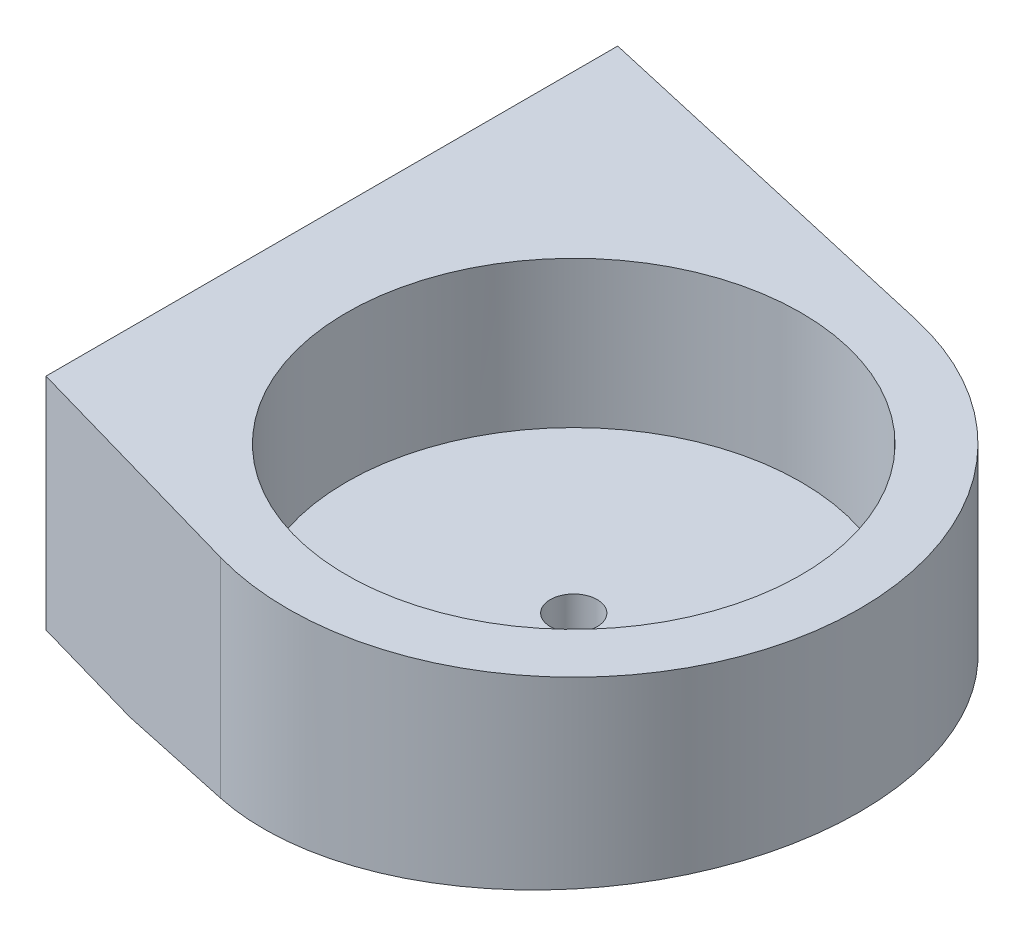
SolidWorks part; units mm, degrees
ref_plane "Front" through (0, 0, 0) normal (0, 0, 1) x (1, 0, 0)
ref_plane "Top" through (0, 0, 0) normal (0, 1, 0) x (1, 0, 0)
ref_plane "Right" through (0, 0, 0) normal (1, 0, 0) x (0, 0, -1)
sketch "Sketch1" plane through (0, 0, 0) normal (0, 1, 0) x (1, 0, 0)
  circle A0 centre (0, 0) radius 15.5
  dimension "D1" = 31
extrude "Boss-Extrude1" add sketch "Sketch1" along normal blind 5
sketch "Sketch2" plane through (0, 0, 0) normal (0, -1, 0) x (1, 0, 0)
  line L0 (-5.3514, 18.7513) -> (-22, 14)
  line L1 (-22, 14) -> (-22, -25)
  line L2 (-22, -25) -> (4.3235, -19.0147)
  circle A3 centre (0, 0) radius 19.5
  arc A4 (4.3235, -19.0147) -> (-5.3514, 18.7513) centre (0, 0) ccw
  point P4 (0, 0)
  point P5 (-25, -28.3121)
  circle M5 centre (0, 0) radius 15.5
  dimension "D4" = 14
  dimension "D2" = 22
  dimension "D3" = 39
  dimension "D1" = 4
extrude "Boss-Extrude2" add sketch "Sketch2" against normal blind 15 contours L2 A4 L0 L1 M5
sketch "Sketch17" plane through (0, 0, 0) normal (0, 0, 1) x (1, 0, 0)
  line L0 (-22, 0) -> (-14, 0)
  line L1 (-5.3514, 0) -> (-22, 0) construction
  line L2 (-14, 0) -> (19.5, 3)
  line L3 (19.5, 0) -> (19.5, 15) construction
  line L4 (19.5, 3) -> (19.5, 0)
  line L5 (19.5, 0) -> (-14, 0)
  line L6 (19.5, 15) -> (-5.3514, 15) construction
  dimension "D1" = 8
  dimension "D2" = 12
extrude "Cut-Extrude7" cut sketch "Sketch17" against normal through all and the other way through all contours L5 L4 L2
sketch "Sketch18" plane through (0, 5, 0) normal (0, 1, 0) x (1, 0, 0)
  circle A0 centre (0, 0) radius 1.6
  dimension "D1" = 3.2
extrude "Cut-Extrude8" cut sketch "Sketch18" against normal through all contours A0
sketch "Sketch19" plane through (0, 0, 0) normal (0, -1, 0) x (1, 0, 0)
  line L0 (-22, -5.5) -> (-18, -5.5) construction
  line L1 (-22, 14) -> (-22, -25) construction
  circle A0 centre (-18, -5.5) radius 2.05
  dimension "D2" = 4.1
  dimension "D1" = 4
extrude "Cut-Extrude9" cut sketch "Sketch19" against normal blind 6
ref_plane "Plane5" through (0, 2, 0) normal (0, 1, 0) x (1, 0, 0)
sketch "Sketch20" plane through (0, 2, 0) normal (0, 1, 0) x (1, 0, 0)
  circle A0 centre (0, 0) radius 4
  dimension "D1" = 8
extrude "Cut-Extrude10" cut sketch "Sketch20" against normal up to next
